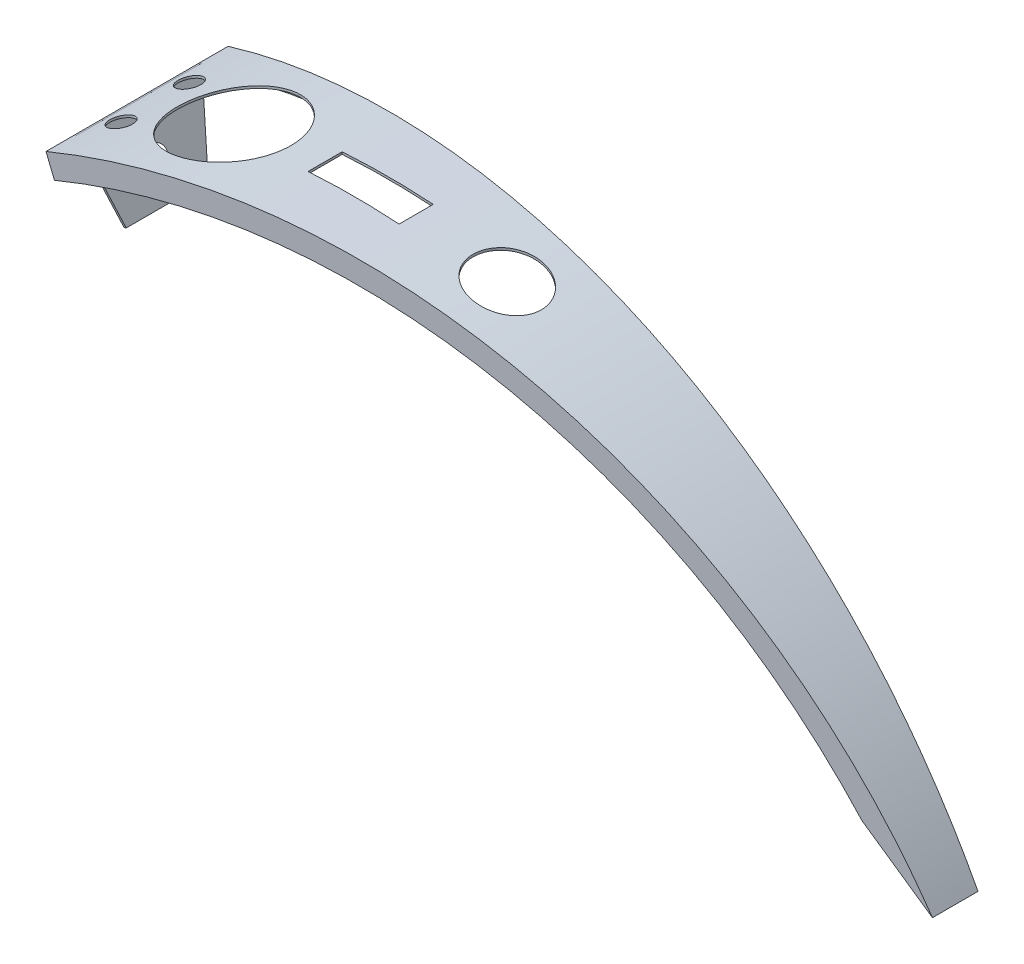
SolidWorks part; units mm, degrees
ref_plane "前视基准面" through (0, 0, 0) normal (0, 0, 1) x (1, 0, 0)
ref_plane "上视基准面" through (0, 0, 0) normal (0, 1, 0) x (1, 0, 0)
ref_plane "右视基准面" through (0, 0, 0) normal (1, 0, 0) x (0, 0, -1)
sketch "草图1" plane through (0, 0, 0) normal (0, 0, 1) x (1, 0, 0)
  line L3 (-102.606, 281.9078) -> (-99.1858, 272.5109)
  line L4 (256.7909, 155.1078) -> (248.2312, 149.9375)
  arc A0 (-102.606, 281.9078) -> (256.7909, 155.1078) centre (0, 0) cw
  arc A1 (-99.1858, 272.5109) -> (248.2312, 149.9375) centre (0, 0) cw
  dimension "D3" = 300
  dimension "D4" = 290
  dimension "D1" = 10
  dimension "D2" = 10
extrude "凸台-拉伸1" add sketch "草图1" along normal mid plane 80
sketch "草图2" plane through (0, 0, 0) normal (0, 1, 0) x (1, 0, 0)
  line L0 (-102.606, 40) -> (256.7909, 40)
  line L1 (256.7909, 40) -> (256.7909, 10)
  line L2 (256.7909, -40) -> (256.7909, 40) construction
  line L3 (256.7909, 10) -> (-102.606, 40)
  line L4 (-82.5344, 0) -> (82.5344, 0) construction
  line L5 (256.7909, -40) -> (256.7909, -10)
  line L6 (-102.606, -40) -> (256.7909, -40)
  line L7 (256.7909, -10) -> (-102.606, -40)
  dimension "D1" = 30
extrude "切除-拉伸1" cut sketch "草图2" along normal through all
shell "抽壳2" thickness 1
sketch "草图3" plane through (0, 0, 0) normal (0, 1, 0) x (1, 0, 0)
  line L1 (-20, -7.5) -> (20, -7.5)
  line L2 (-20, -7.5) -> (-20, 7.5)
  line L3 (-20, 7.5) -> (20, 7.5)
  line L4 (20, -7.5) -> (20, 7.5)
  line L5 (-20, -7.5) -> (20, 7.5) construction
  line L6 (-20, 7.5) -> (20, -7.5) construction
  point P0 (0, 0)
  dimension "D1" = 15
  dimension "D2" = 40
extrude "切除-拉伸2" cut sketch "草图3" along normal through all
sketch "草图4" plane through (0, 0, 0) normal (0, 1, 0) x (1, 0, 0)
  line L0 (-102.606, 0) -> (-91.425, 0) construction
  line L1 (-102.606, -40) -> (-102.606, 40) construction
  circle A0 centre (-60, 0) radius 25
  circle A1 centre (60, 0) radius 15
  circle A2 centre (-94.606, 15) radius 5
  circle A3 centre (-94.606, -15) radius 5
  dimension "D2" = 50
  dimension "D3" = 8
  dimension "D1" = 30
extrude "切除-拉伸3" cut sketch "草图4" along normal through all contours A0 | A1 | A2 | A3
sketch "草图5" plane through (0, 0, 0) normal (0, 0, 1) x (1, 0, 0)
  line L0 (256.7909, 155.1078) -> (228.2749, 178.8591)
  line L1 (228.2749, 178.8591) -> (202.0853, 147.4157)
  line L2 (202.0853, 147.4157) -> (242.5329, 124.0674)
  line L3 (242.5329, 124.0674) -> (256.7909, 155.1078)
  arc A1 (248.2312, 149.9375) -> (-99.1858, 272.5109) centre (0, 0) ccw construction
extrude "切除-拉伸4" cut sketch "草图5" against normal mid plane 80
ref_plane "基准面1" through (0, 0, 0) normal (-0.9397, -0.342, 0) x (0, 0, 1)
sketch "草图6" plane through (0, 0, 0) normal (-0.9397, -0.342, 0) x (0, 0, 1)
  line L1 (-27.5, 300) -> (-18, 264)
  line L2 (-18, 264) -> (18, 264)
  line L3 (18, 264) -> (27.5, 300)
  line L5 (-27.5, 300) -> (27.5, 300)
  line L7 (0, 231.247) -> (0, 317.6839) construction
  line L8 (40, 300) -> (-40, 300) construction
  dimension "D1" = 55
  dimension "D2" = 36
  dimension "D3" = 36
extrude "凸台-拉伸2" add sketch "草图6" against normal blind 1
sketch "草图7" plane through (0, 0, 0) normal (-0.9397, -0.342, 0) x (0, 0, 1)
  circle A0 centre (0, 279.2386) radius 5
  dimension "D1" = 10
extrude "切除-拉伸5" cut sketch "草图7" against normal blind 1
hole_wizard "大小mm 暗销孔1" positions "草图8" profile "草图9" hole size "Ø1.0" standard "GB"
sketch "草图8" plane through (0, 0, 0) normal (-0.9397, -0.342, 0) x (0, 0, 1)
  point P0 (0, 279.2386)
sketch "草图9" plane through (-95.5052, 262.3984, 0) normal (0, 0, 1) x (0.342, -0.9397, 0)
  line L0 (0, 0) -> (0, 12.7004)
  line L1 (0, 12.7004) -> (0.5, 12.4)
  line L2 (0.5, 12.4) -> (0.5, 5.9)
  line L3 (0.5, 5.9) -> (6.4, 0)
  line L5 (6.4, 0) -> (0, 0)
  line L6 (-0.5, 5.9) -> (-6.4, 0) construction
  line L10 (0, 12.7004) -> (-0.5, 12.4) construction
  line L11 (0, -6.35) -> (0, 107.95) construction
  dimension "孔直径" = 1
  dimension "孔深度" = 12.4
  dimension "近端锥形沉头孔直径" = 12.8
  dimension "近端锥形沉头孔角度" = 90
  dimension "导头角度" = 118
sketch "草图10" plane through (0, 0, 0) normal (-0.9397, -0.342, 0) x (0, 0, 1)
  line L0 (-40, 300) -> (40, 300)
ref_plane "基准面2" through (-102.606, 281.9078, 0) normal (-0.342, 0.9397, 0) x (0.9397, 0.342, 0)
